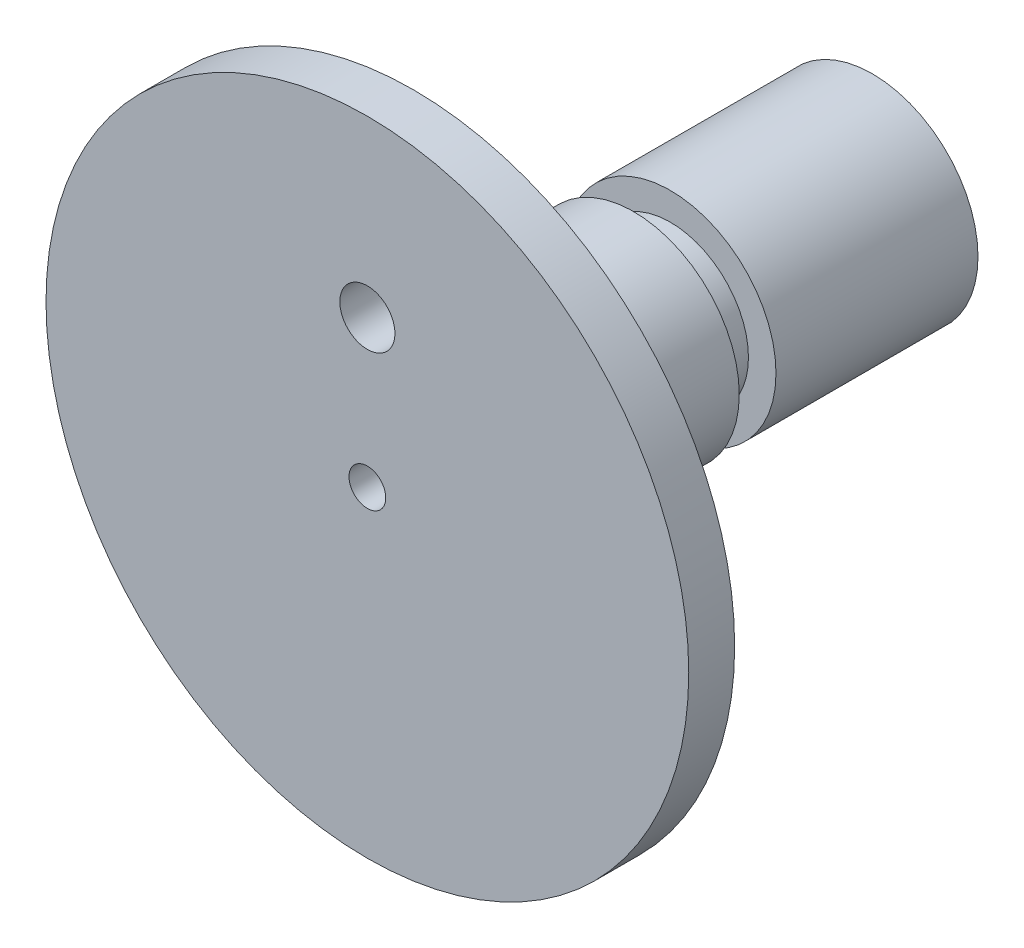
SolidWorks part; units mm, degrees
ref_plane "Alzado" through (0, 0, 0) normal (0, 0, 1) x (1, 0, 0)
ref_plane "Planta" through (0, 0, 0) normal (0, 1, 0) x (1, 0, 0)
ref_plane "Vista lateral" through (0, 0, 0) normal (1, 0, 0) x (0, 0, -1)
sketch "Croquis2" plane through (0, 0, 0) normal (0, 0, 1) x (1, 0, 0)
  circle A0 centre (0, 0) radius 17.5
  dimension "D1" = 35
extrude "Saliente-Extruir1" add sketch "Croquis2" along normal mid plane 2.5
sketch "Croquis3" plane through (0, 0, -1.25) normal (0, 0, -1) x (-1, 0, 0)
  line L0 (0, 7.5996) -> (0, -8.5454) construction
  line L1 (-1.95, 1.9391) -> (-1.95, -1.9391)
  line L2 (1.95, 1.9391) -> (1.95, -1.9391)
  circle A0 centre (0, 0) radius 2.75
  circle A1 centre (0, 0) radius 5.75
  dimension "D1" = 5.5
  dimension "D2" = 3
  dimension "D3" = 3.9
extrude "Saliente-Extruir2" add sketch "Croquis3" along normal blind 25 contours L0 A1 A0 | A1 L0 A0 | L1 A0 | L2 A0
sketch "Croquis4" plane through (0, 0, 1.25) normal (0, 0, 1) x (1, 0, 0)
  circle A0 centre (0, 0) radius 1
  dimension "D1" = 2
extrude "Cortar-Extruir1" cut sketch "Croquis4" against normal blind 15
sketch "Croquis7" plane through (0, 0, 1.25) normal (0, 0, 1) x (1, 0, 0)
  line L0 (0, 0) -> (0, 8) construction
  circle A0 centre (0, 8) radius 1.5
  dimension "D1" = 3
  dimension "D2" = 8
extrude "Cortar-Extruir2" cut sketch "Croquis7" against normal blind 10
sketch "Croquis8" plane through (0, 0, 0) normal (0, 1, 0) x (1, 0, 0)
  line L0 (0, 0) -> (0, 24.7224) construction
  line L1 (5.75, 1.25) -> (5.75, 26.25) construction
  line L2 (5.75, 1.25) -> (5.75, 26.25) construction
  line L3 (17.5, 1.25) -> (-17.5, 1.25) construction
  line L4 (5.75, 15.25) -> (4.25, 15.25)
  line L5 (5.75, 15.25) -> (5.75, 13.25)
  line L6 (5.75, 13.25) -> (4.25, 13.25)
  line L7 (4.25, 15.25) -> (4.25, 13.25)
  line L9 (5.75, 9.25) -> (4.75, 9.25)
  line L10 (5.75, 9.25) -> (5.75, 7.25)
  line L11 (5.75, 7.25) -> (4.75, 7.25)
  line L12 (4.75, 9.25) -> (4.75, 7.25)
  dimension "D1" = 1.5
  dimension "D2" = 2
  dimension "D3" = 12
  dimension "D4" = 1
  dimension "D5" = 2
  dimension "D6" = 6
revolve "Cortar-Revolución1" cut sketch "Croquis8" angle 360 about L0
